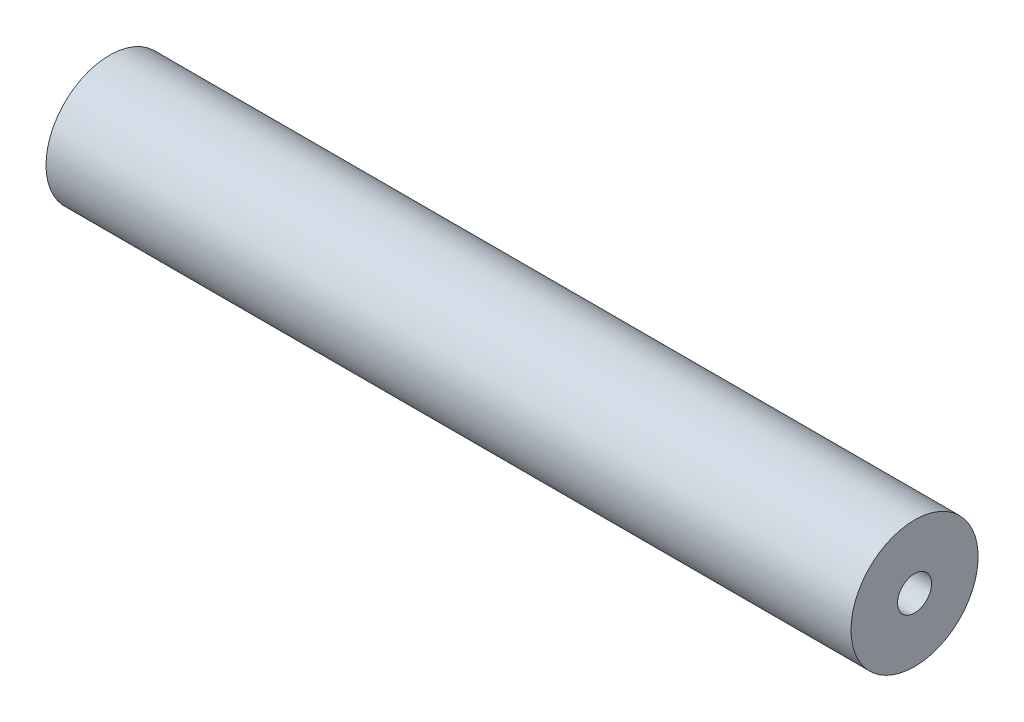
SolidWorks part; units mm, degrees
material "6061-T6 (SS)"
ref_plane "Front Plane" through (0, 0, 0) normal (0, 0, 1) x (1, 0, 0)
ref_plane "Top Plane" through (0, 0, 0) normal (0, 1, 0) x (1, 0, 0)
ref_plane "Right Plane" through (0, 0, 0) normal (1, 0, 0) x (0, 0, -1)
sketch "Sketch1" plane through (0, 0, 0) normal (1, 0, 0) x (0, 0, -1)
  circle A0 centre (0, 0) radius 9.525
  dimension "D1" = 19.05
extrude "Boss-Extrude1" add sketch "Sketch1" along normal mid plane 120.65
hole_wizard "1/4-20 Tapped Hole1" positions "3DSketch1" profile "Sketch2" tap size "1/4-20" standard "ANSI Inch"
sketch3d "3DSketch1"
  line L0 (60.325, 0, 0) -> (-60.325, 0, 0) construction
  point P0 (60.325, 0, 0)
  point P4 (-60.325, 0, 0)
sketch "Sketch2" plane through (60.325, 0, 0) normal (0, 1, 0) x (0, 0, -1)
  line L0 (0, 0) -> (0, 18.0438)
  line L1 (0, 18.0438) -> (2.5527, 16.51)
  line L2 (2.5527, 16.51) -> (2.5527, 0)
  line L5 (2.5527, 0) -> (0, 0)
  line L10 (0, 18.0438) -> (-2.5527, 16.51) construction
  line L11 (0, -6.35) -> (0, 107.95) construction
  dimension "Tap Drill Dia." = 5.1054
  dimension "Tap Drill Depth" = 16.51
  dimension "Drill Angle" = 118
cosmetic thread "Hole Thread1"
cosmetic thread "Hole Thread2"
